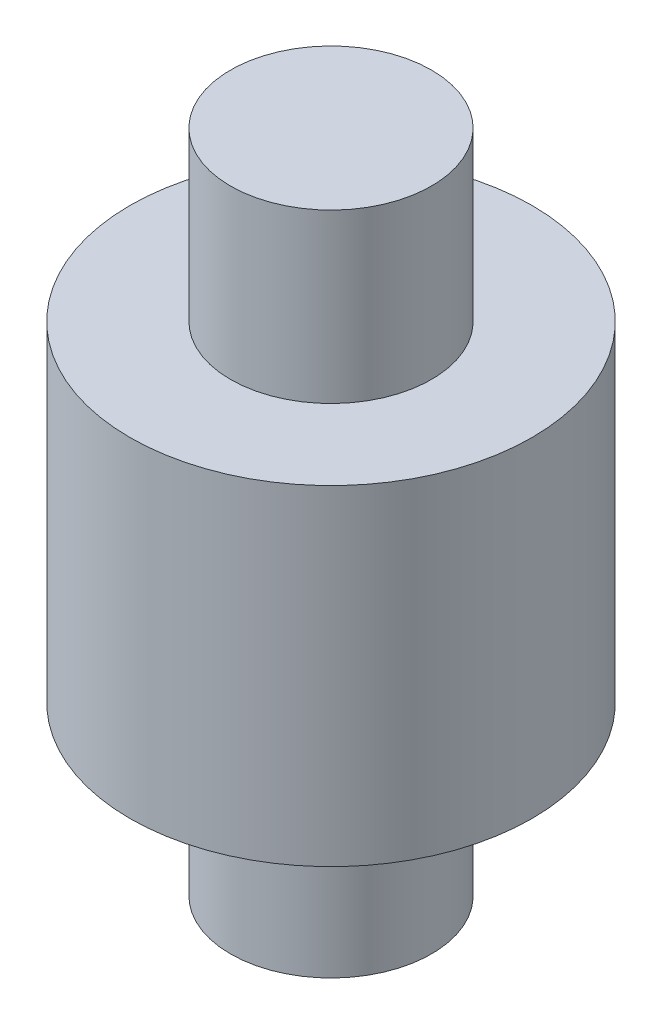
SolidWorks part; units mm, degrees
material "6061-T6 (SS)"
ref_plane "Front Plane" through (0, 0, 0) normal (0, 0, 1) x (1, 0, 0)
ref_plane "Top Plane" through (0, 0, 0) normal (0, 1, 0) x (1, 0, 0)
ref_plane "Right Plane" through (0, 0, 0) normal (1, 0, 0) x (0, 0, -1)
ref_plane "Plane1" through (0, 0, 0) normal (0, 0, -1) x (-1, 0, 0)
sketch "Sketch1" plane through (0, 0, 0) normal (0, 0, -1) x (-1, 0, 0)
  line L0 (-1.524, 0) -> (0, 0)
  line L1 (0, 0) -> (0, 10.0838)
  line L2 (0, 10.0838) -> (-1.524, 10.0838)
  line L3 (-1.524, 10.0838) -> (-1.524, 7.5438)
  line L4 (-1.524, 7.5438) -> (-3.048, 7.5438)
  line L5 (-3.048, 7.5438) -> (-3.048, 2.54)
  line L6 (-3.048, 2.54) -> (-1.524, 2.54)
  line L7 (-1.524, 2.54) -> (-1.524, 0)
  line L8 (0, 0) -> (0, 10.0838) construction
revolve "Revolve1" add sketch "Sketch1" angle 360 about L8
